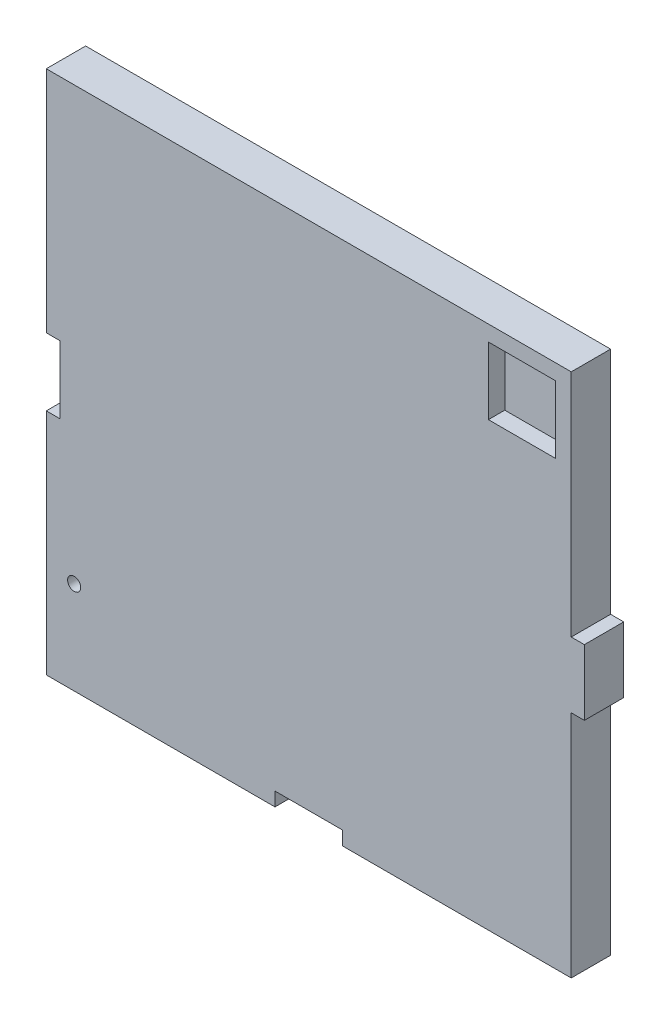
SolidWorks part; units mm, degrees
ref_plane "Front Plane" through (0, 0, 0) normal (0, 0, 1) x (1, 0, 0)
ref_plane "Top Plane" through (0, 0, 0) normal (0, 1, 0) x (1, 0, 0)
ref_plane "Right Plane" through (0, 0, 0) normal (1, 0, 0) x (0, 0, -1)
sketch "Sketch1" plane through (0, 0, 0) normal (0, 0, 1) x (1, 0, 0)
  line L0 (0, 0) -> (69.7, 0)
  line L1 (69.7, 0) -> (69.7, 4.2)
  line L2 (69.7, 4.2) -> (90.3, 4.2)
  line L3 (90.3, 4.2) -> (90.3, 0)
  line L4 (90.3, 0) -> (160, 0)
  line L5 (160, 0) -> (160, 70)
  line L6 (160, 70) -> (164, 70)
  line L7 (164, 70) -> (164, 90)
  line L8 (164, 90) -> (160, 90)
  line L9 (160, 90) -> (160, 160)
  line L10 (160, 160) -> (90, 160)
  line L11 (90, 160) -> (70, 160)
  line L14 (70, 160) -> (0, 160)
  line L15 (0, 160) -> (0, 90.3)
  line L16 (0, 90.3) -> (4.2, 90.3)
  line L17 (4.2, 90.3) -> (4.2, 69.7)
  line L18 (4.2, 69.7) -> (0, 69.7)
  line L19 (0, 69.7) -> (0, 0)
  circle A0 centre (8.5, 28.3) radius 2
  dimension "D1" = 4
extrude "Boss-Extrude1" add sketch "Sketch1" along normal blind 12
sketch "Sketch2" plane through (0, 0, 12) normal (0, 0, 1) x (1, 0, 0)
  line L0 (134.75, 134.75) -> (155.25, 134.75)
  line L1 (155.25, 134.75) -> (155.25, 155.25)
  line L2 (155.25, 155.25) -> (134.75, 155.25)
  line L3 (134.75, 155.25) -> (134.75, 134.75)
extrude "Cut-Extrude1" cut sketch "Sketch2" against normal blind 5
sketch "Sketch4" plane through (0, 0, 0) normal (0, 0, -1) x (-1, 0, 0)
  circle A0 centre (-8.5, 28.3) radius 3.45
  dimension "D1" = 6.9
extrude "Cut-Extrude3" cut sketch "Sketch4" against normal blind 8
